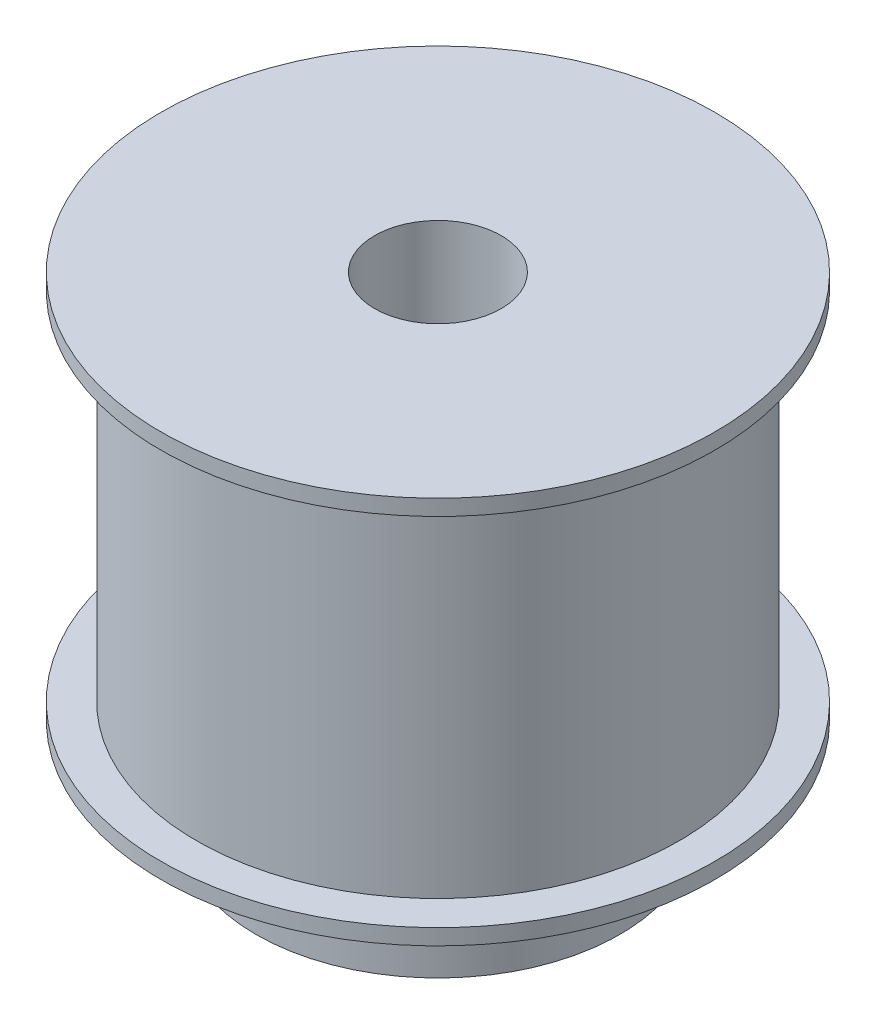
SolidWorks part; units mm, degrees
ref_plane "Front Plane" through (0, 0, 0) normal (0, 0, 1) x (1, 0, 0)
ref_plane "Top Plane" through (0, 0, 0) normal (0, 1, 0) x (1, 0, 0)
ref_plane "Right Plane" through (0, 0, 0) normal (1, 0, 0) x (0, 0, -1)
sketch "Sketch2" plane through (0, 0, 0) normal (0, 0, 1) x (1, 0, 0)
  line L0 (-11.5, 0) -> (0, 0) construction
  line L2 (0, 0) -> (0, -6)
  line L3 (0, -6) -> (-11.5, -6)
  line L4 (-11.5, 0) -> (-11.5, -6)
  line L5 (-11.5, 0) -> (-17.5, 0)
  line L6 (0, 0) -> (0, 1)
  line L7 (-15.25, 1) -> (-17.5, 1)
  line L8 (-17.5, 0) -> (-17.5, 1)
  line L10 (0, 1) -> (0, 23.5)
  line L12 (-15.25, 1) -> (-15.25, 23.5)
  line L13 (-15.25, 1) -> (0, 1) construction
  line L14 (-15.25, 12.25) -> (0, 12.25) construction
  line L15 (-15.25, 23.5) -> (0, 23.5) construction
  line L16 (-15.25, 23.5) -> (-17.5, 23.5)
  line L17 (0, 23.5) -> (0, 24.5)
  line L18 (0, 24.5) -> (-17.5, 24.5)
  line L19 (-17.5, 23.5) -> (-17.5, 24.5)
  dimension "D1" = 6
  dimension "D2" = 11.5
  dimension "D3" = 1
  dimension "D4" = 17.5
  dimension "D5" = 22.5
  dimension "D6" = 15.25
  dimension "D7" = 1
  dimension "D8" = 17.5
revolve "Revolve1" add sketch "Sketch2" angle 360 about L10
sketch "Sketch3" plane through (0, 24.5, 0) normal (0, 1, 0) x (1, 0, 0)
  circle A0 centre (0, 0) radius 4
  dimension "D1" = 8
extrude "Cut-Extrude1" cut sketch "Sketch3" against normal blind 30.5
